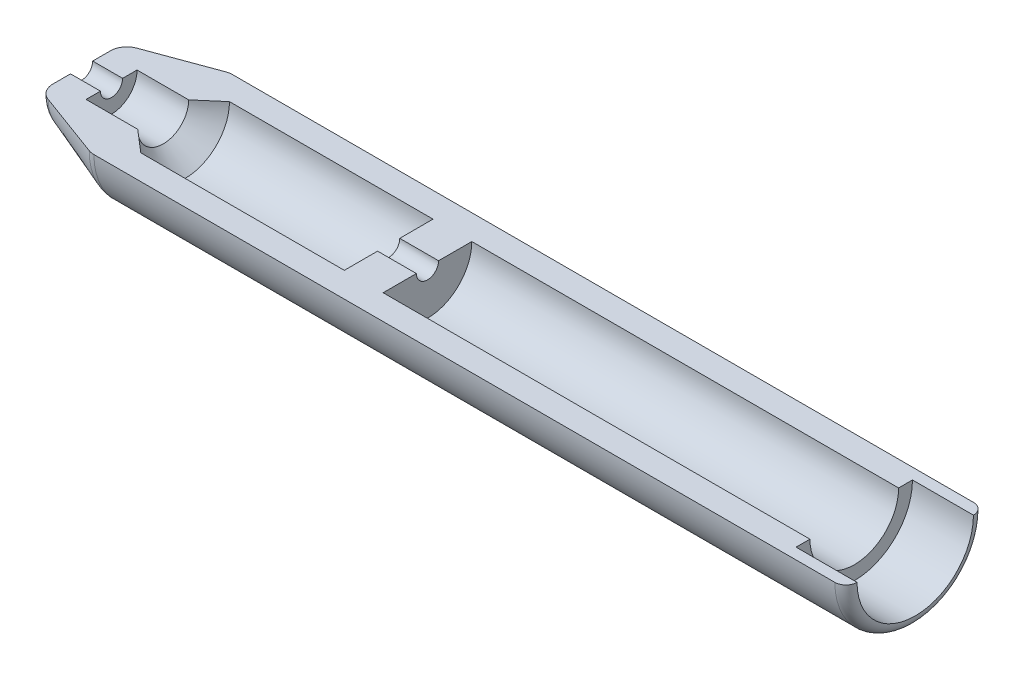
SolidWorks part; units mm, degrees
ref_plane "Front Plane" through (0, 0, 0) normal (0, 0, 1) x (1, 0, 0)
ref_plane "Top Plane" through (0, 0, 0) normal (0, 1, 0) x (1, 0, 0)
ref_plane "Right Plane" through (0, 0, 0) normal (1, 0, 0) x (0, 0, -1)
sketch "Sketch1" plane through (0, 0, 0) normal (0, 1, 0) x (1, 0, 0)
  line L0 (-3.185, 0.1) -> (19.4194, 0.1) construction
  line L1 (-2.4261, 0.9) -> (-1.2536, 1.3315)
  line L2 (12.4176, 1.15) -> (11.3176, 1.15)
  line L3 (11.3176, 1.15) -> (11.3176, 0.9)
  line L5 (2.9176, 0.9) -> (2.9176, 0.3)
  line L6 (2.9176, 0.3) -> (3.6176, 0.3)
  line L7 (-2.0824, 0.3) -> (-2.0824, 0.56)
  line L8 (3.6176, 0.3) -> (3.6176, 0.9)
  line L9 (3.6176, 0.9) -> (11.3176, 0.9)
  line L14 (-2.0824, 0.3) -> (-2.6225, 0.3)
  line L16 (-2.0824, 0.56) -> (-1.15, 0.56)
  line L23 (-1.15, 0.56) -> (-0.7544, 0.9)
  line L24 (12.4176, 5.6171) -> (12.4176, -3.3829) construction
  line L25 (-0.7544, 0.9) -> (2.9176, 0.9)
  line L27 (12.2176, 1.35) -> (-1.15, 1.35)
  line L28 (-2.6225, 0.6185) -> (-2.6225, 0.3)
  arc A0 (-2.4261, 0.9) -> (-2.6225, 0.6185) centre (-2.3225, 0.6185) ccw
  arc A1 (-1.2536, 1.3315) -> (-1.15, 1.35) centre (-1.15, 1.05) cw
  arc A2 (12.2176, 1.35) -> (12.4176, 1.15) centre (12.2176, 1.15) cw
  point P0 (0, 0)
  point P16 (12.4176, 1.35)
  point P24 (12.4176, 1.35)
  dimension "D2" = 0.3
  dimension "D5" = 0.3
  dimension "D6" = 0.46
  dimension "D9" = 0.2
  dimension "D1" = 0.2
  dimension "D3" = 1.25
  dimension "D4" = 0.8
  dimension "D7" = 1.05
  dimension "D8" = 14.5
  dimension "D10" = 1.1
  dimension "D11" = 5
revolve "Revolve1" add sketch "Sketch1" angle 180 about L0
